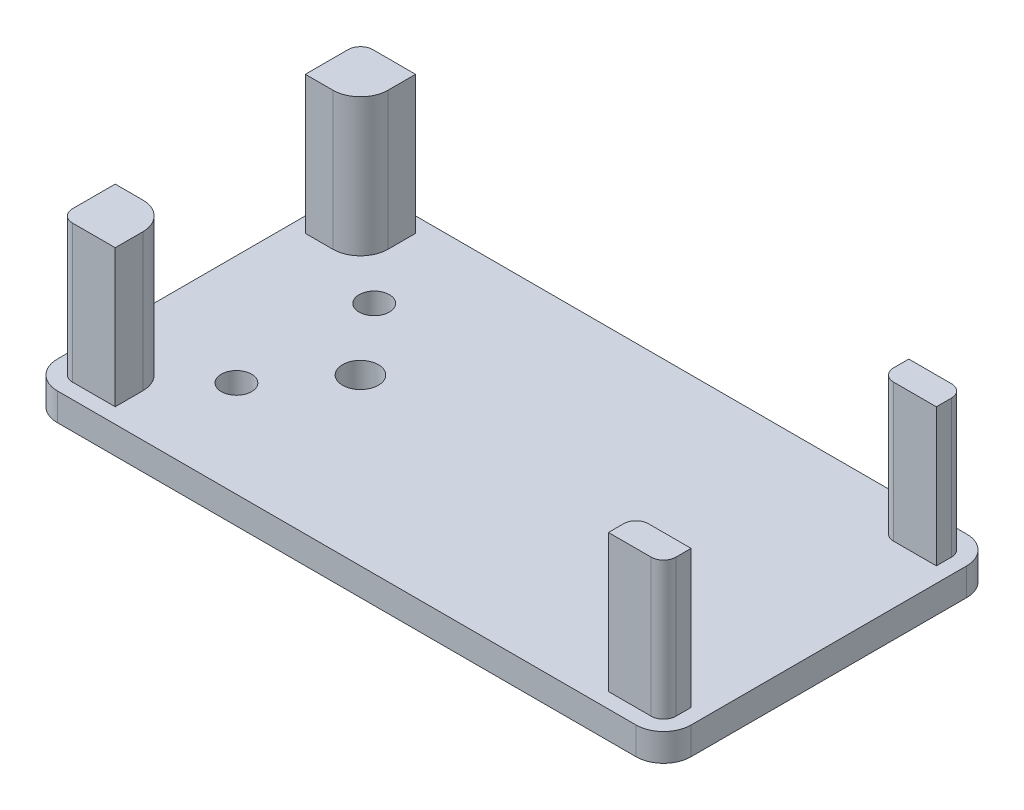
SolidWorks part; units mm, degrees
ref_plane "Front Plane" through (0, 0, 0) normal (0, 0, 1) x (1, 0, 0)
ref_plane "Top Plane" through (0, 0, 0) normal (0, 1, 0) x (1, 0, 0)
ref_plane "Right Plane" through (0, 0, 0) normal (1, 0, 0) x (0, 0, -1)
sketch "Sketch1" plane through (0, 0, 0) normal (0, 1, 0) x (1, 0, 0)
  line L1 (0, 0) -> (111.76, 0)
  line L2 (0, 0) -> (0, 60.96)
  line L3 (0, 60.96) -> (111.76, 60.96)
  line L4 (111.76, 0) -> (111.76, 60.96)
  dimension "D1" = 60.96
  dimension "D2" = 111.76
extrude "Boss-Extrude1" add sketch "Sketch1" along normal blind 5.08
fillet "Fillet1" radius 5.08 4 edges at (0, 2.54, -60.96) (111.76, 2.54, -60.96) (111.76, 2.54, 0) (0, 2.54, 0)
sketch "Sketch2" plane through (0, 5.08, 0) normal (0, 1, 0) x (1, 0, 0)
  line L0 (58.42, 60.96) -> (58.42, 0) construction
  line L1 (2.794, 58.166) -> (12.954, 58.166)
  line L2 (2.794, 58.166) -> (2.794, 48.006)
  line L3 (2.794, 48.006) -> (12.954, 48.006)
  line L4 (12.954, 58.166) -> (12.954, 48.006)
  line L7 (0, 30.48) -> (111.76, 30.48) construction
  line L8 (0, 55.88) -> (0, 5.08) construction
  line L9 (111.76, 5.08) -> (111.76, 55.88) construction
  line L18 (12.954, 2.794) -> (12.954, 12.954)
  line L19 (2.794, 12.954) -> (12.954, 12.954)
  line L20 (2.794, 2.794) -> (2.794, 12.954)
  line L21 (2.794, 2.794) -> (12.954, 2.794)
  line L30 (106.68, 60.96) -> (5.08, 60.96) construction
  line L31 (5.08, 0) -> (106.68, 0) construction
  line L33 (103.886, 58.166) -> (114.046, 58.166)
  line L34 (103.886, 58.166) -> (103.886, 53.086)
  line L35 (103.886, 53.086) -> (114.046, 53.086)
  line L36 (114.046, 58.166) -> (114.046, 53.086)
  line L37 (103.886, 2.794) -> (114.046, 2.794)
  line L38 (103.886, 2.794) -> (103.886, 7.874)
  line L39 (103.886, 7.874) -> (114.046, 7.874)
  line L40 (114.046, 2.794) -> (114.046, 7.874)
  dimension "D1" = 2.794
  dimension "D2" = 2.794
  dimension "D3" = 10.16
  dimension "D4" = 10.16
  dimension "D5" = 58.42
  dimension "D6" = 55.626
  dimension "D7" = 10.16
  dimension "D8" = 5.08
  dimension "D9" = 5.08
  dimension "D10" = 2.794
  dimension "D11" = 2.794
sketch "Sketch3" plane through (0, 0, 0) normal (0, -1, 0) x (1, 0, 0)
  circle A0 centre (20.32, -17.78) radius 2.794
  circle A1 centre (20.32, -43.18) radius 2.794
  circle A2 centre (30.48, -30.48) radius 3.302
  dimension "D1" = 5.588
  dimension "D2" = 5.588
  dimension "D3" = 6.604
  dimension "D4" = 10.16
  dimension "D5" = 25.4
  dimension "D6" = 17.78
  dimension "D7" = 12.7
  dimension "D8" = 20.32
extrude "Cut-Extrude1" cut sketch "Sketch3" against normal up to next
sketch "Sketch5" plane through (0, 0, 0) normal (0, -1, 0) x (1, 0, 0)
  line L1 (106.68, 0) -> (116.84, 0)
  line L2 (106.68, 0) -> (106.68, -60.96)
  line L3 (106.68, -60.96) -> (116.84, -60.96)
  line L4 (116.84, 0) -> (116.84, -60.96)
  dimension "D1" = 10.16
extrude "Boss-Extrude2" add sketch "Sketch5" against normal blind 5.08
fillet "Fillet2" radius 5.08 2 edges at (116.84, 2.54, -60.96) (116.84, 2.54, 0)
extrude "Boss-Extrude5" add sketch "Sketch2" along normal blind 25.4
fillet "Fillet9" radius 2.286 6 edges at (114.046, 17.78, -2.794) (103.886, 17.78, -7.874) (114.046, 17.78, -58.166) (103.886, 17.78, -53.086) (2.794, 17.78, -2.794) (2.794, 17.78, -58.166)
fillet "Fillet10" radius 5.08 2 edges at (12.954, 17.78, -12.954) (12.954, 17.78, -48.006)
